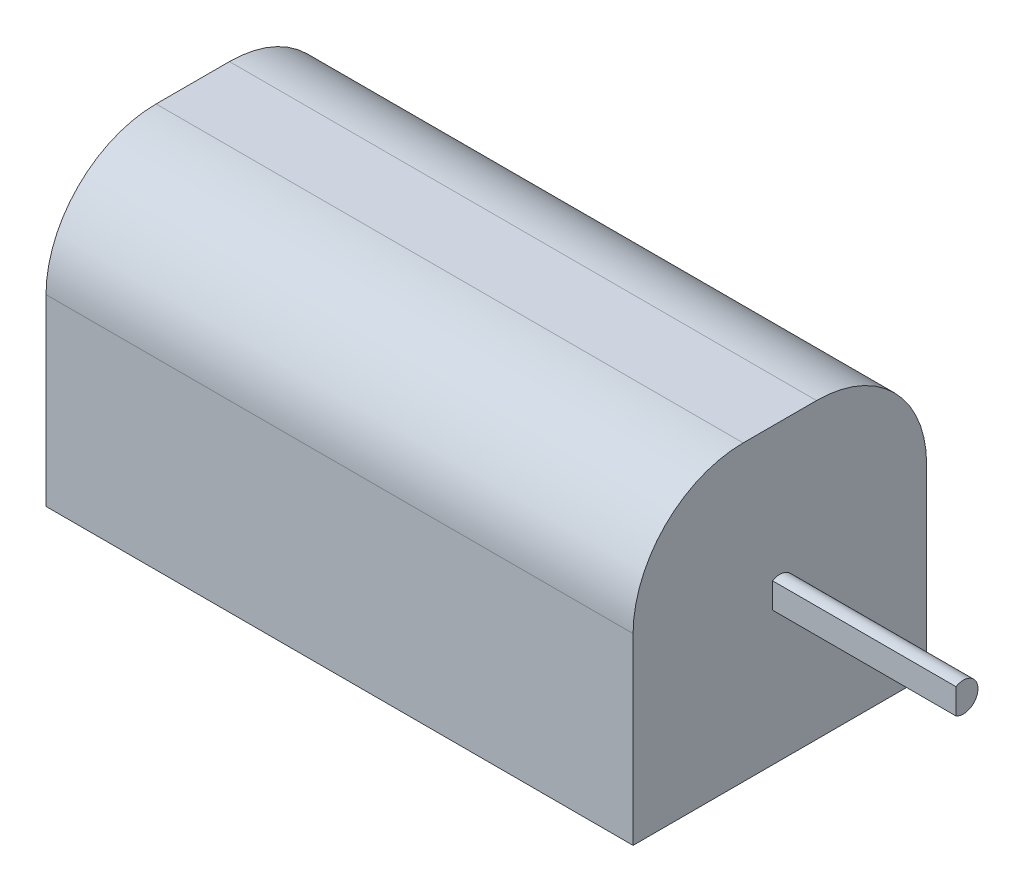
SolidWorks part; units mm, degrees
ref_plane "Front Plane" through (0, 0, 0) normal (0, 0, 1) x (1, 0, 0)
ref_plane "Top Plane" through (0, 0, 0) normal (0, 1, 0) x (1, 0, 0)
ref_plane "Right Plane" through (0, 0, 0) normal (1, 0, 0) x (0, 0, -1)
sketch "Sketch1" plane through (0, 0, 0) normal (0, 1, 0) x (1, 0, 0)
  line L1 (-40, -20) -> (40, -20)
  line L2 (-40, -20) -> (-40, 20)
  line L3 (-40, 20) -> (40, 20)
  line L4 (40, -20) -> (40, 20)
  line L5 (-40, -20) -> (40, 20) construction
  line L6 (-40, 20) -> (40, -20) construction
  point P0 (0, 0)
  dimension "D1" = 80
  dimension "D2" = 40
extrude "Boss-Extrude1" add sketch "Sketch1" along normal mid plane 40
sketch "Sketch4" plane through (0, 0, 0) normal (1, 0, 0) x (0, 0, -1)
  line L0 (-1, 1.7321) -> (-1, -1.7321)
  circle A0 centre (0, 0) radius 2
  dimension "D1" = 4
  dimension "D2" = 1
extrude "Boss-Extrude2" add sketch "Sketch4" along normal blind 25 from surface at 40 contours L0 A0
fillet "Fillet1" radius 15 2 edges at (0, 20, -20) (0, 20, 20)
